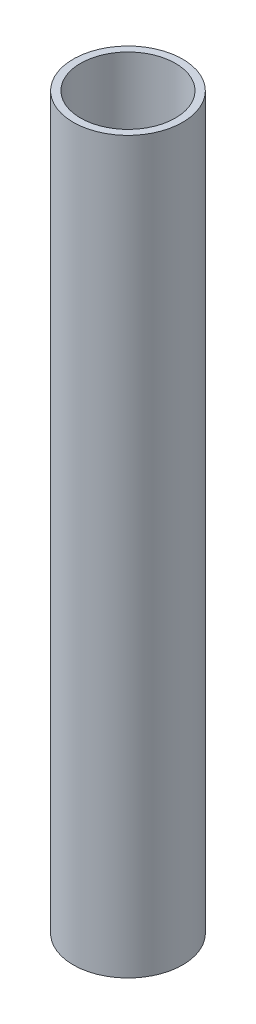
SolidWorks part; units mm, degrees
ref_plane "Front Plane" through (0, 0, 0) normal (0, 0, 1) x (1, 0, 0)
ref_plane "Top Plane" through (0, 0, 0) normal (0, 1, 0) x (1, 0, 0)
ref_plane "Right Plane" through (0, 0, 0) normal (1, 0, 0) x (0, 0, -1)
sketch "Sketch1" plane through (0, 0, 0) normal (0, 1, 0) x (1, 0, 0)
  circle A0 centre (0, 0) radius 7.5
extrude "Extrude-Thin1" add sketch "Sketch1" along normal blind 100 thin thin type one direction reverse wall 1
